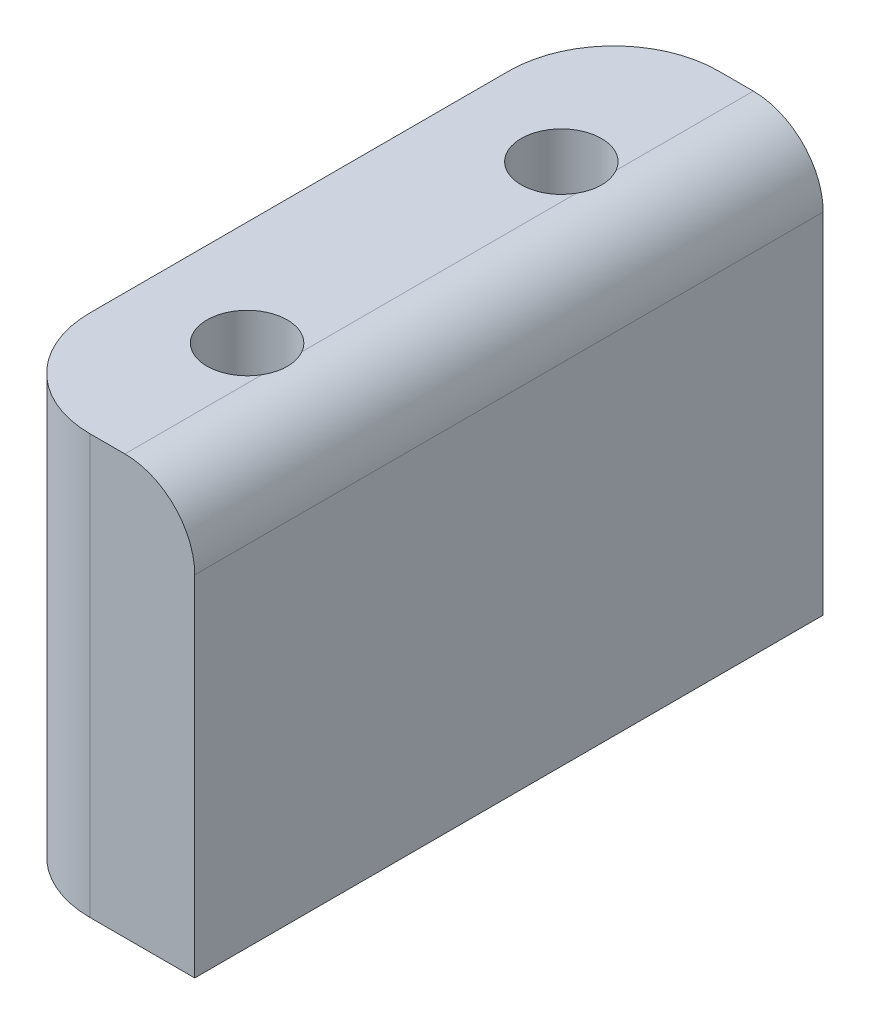
SolidWorks part; units mm, degrees
material "ABS"
ref_plane "前视基准面" through (0, 0, 0) normal (0, 0, 1) x (1, 0, 0)
ref_plane "上视基准面" through (0, 0, 0) normal (0, 1, 0) x (1, 0, 0)
ref_plane "右视基准面" through (0, 0, 0) normal (1, 0, 0) x (0, 0, -1)
sketch "草图1" plane through (0, 0, 0) normal (0, 0, 1) x (1, 0, 0)
  line L4 (6, 0) -> (0, 0)
  line L5 (0, 0) -> (0, 12)
  line L6 (0, 12) -> (4, 12)
  line L7 (6, 10) -> (6, 0)
  line L8 (2, 12) -> (2, 0) construction
  line L9 (6, 10) -> (0, 10) construction
  arc A1 (6, 10) -> (4, 12) centre (4, 10) ccw
  dimension "D3" = 4
  dimension "D1" = 6
  dimension "D2" = 12
  dimension "D4" = 2
extrude "凸台-拉伸1" add sketch "草图1" along normal blind 18
sketch "草图2" plane through (0, 0, 0) normal (0, -1, 0) x (1, 0, 0)
  line L0 (3, 18) -> (3, 0) construction
  line L1 (0, 18) -> (6, 18) construction
  line L2 (0, 0) -> (6, 0) construction
  line L3 (0, 9) -> (6, 9) construction
  line L4 (0, 18) -> (0, 0) construction
  line L5 (6, 18) -> (6, 0) construction
  circle A0 centre (3, 13.5) radius 1.15
  circle A1 centre (3, 4.5) radius 1.15
  dimension "D1" = 2.3
  dimension "D2" = 2.3
  dimension "D3" = 4.5
  dimension "D4" = 4.5
extrude "切除-拉伸1" cut sketch "草图2" against normal blind 16
fillet "圆角1" radius 3 2 edges at (0, 6, 18) (0, 6, 0)
